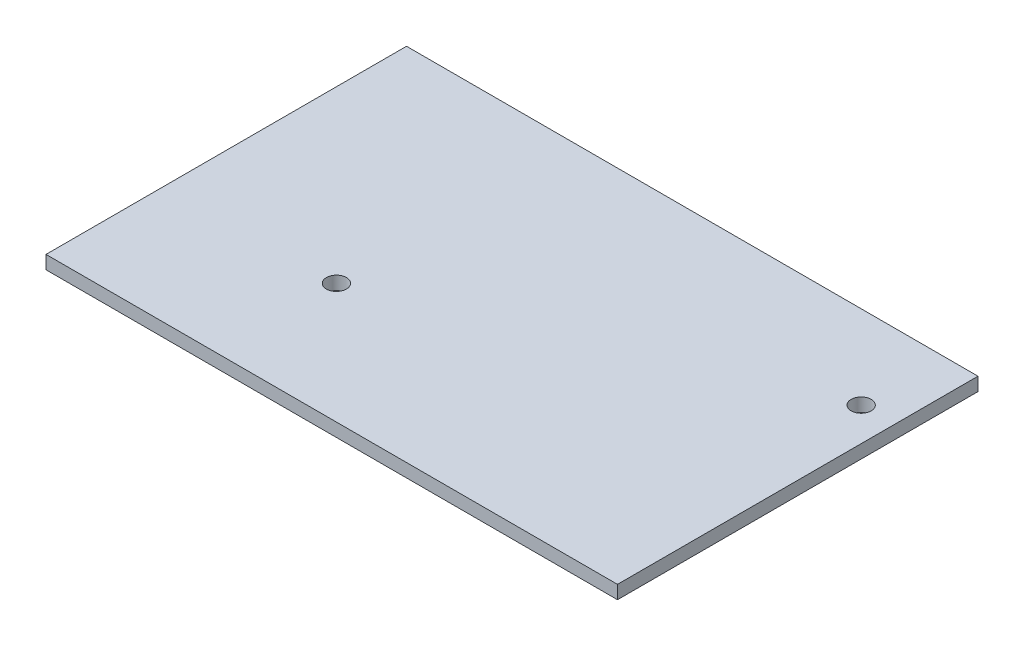
SolidWorks part; units mm, degrees
material "A-Glass Fiber"
ref_plane "Front Plane" through (0, 0, 0) normal (0, 0, 1) x (1, 0, 0)
ref_plane "Top Plane" through (0, 0, 0) normal (0, 1, 0) x (1, 0, 0)
ref_plane "Right Plane" through (0, 0, 0) normal (1, 0, 0) x (0, 0, -1)
sketch "Sketch1" plane through (0, 0, 0) normal (0, 1, 0) x (1, 0, 0)
  line L1 (-136.1887, 61.6415) -> (-50.5887, 61.6415)
  line L2 (-136.1887, 61.6415) -> (-136.1887, 7.6415)
  line L3 (-136.1887, 7.6415) -> (-50.5887, 7.6415)
  line L4 (-50.5887, 61.6415) -> (-50.5887, 7.6415)
  circle A0 centre (-110.6887, 25.6415) radius 1.5
  circle A1 centre (-55.5887, 49.1415) radius 1.5
  dimension "D5" = 3
  dimension "D6" = 3
  dimension "D1" = 54
  dimension "D2" = 85.6
  dimension "D3" = 18
  dimension "D4" = 25.5
  dimension "D7" = 5
  dimension "D8" = 12.5
extrude "Boss-Extrude1" add sketch "Sketch1" along normal blind 2
